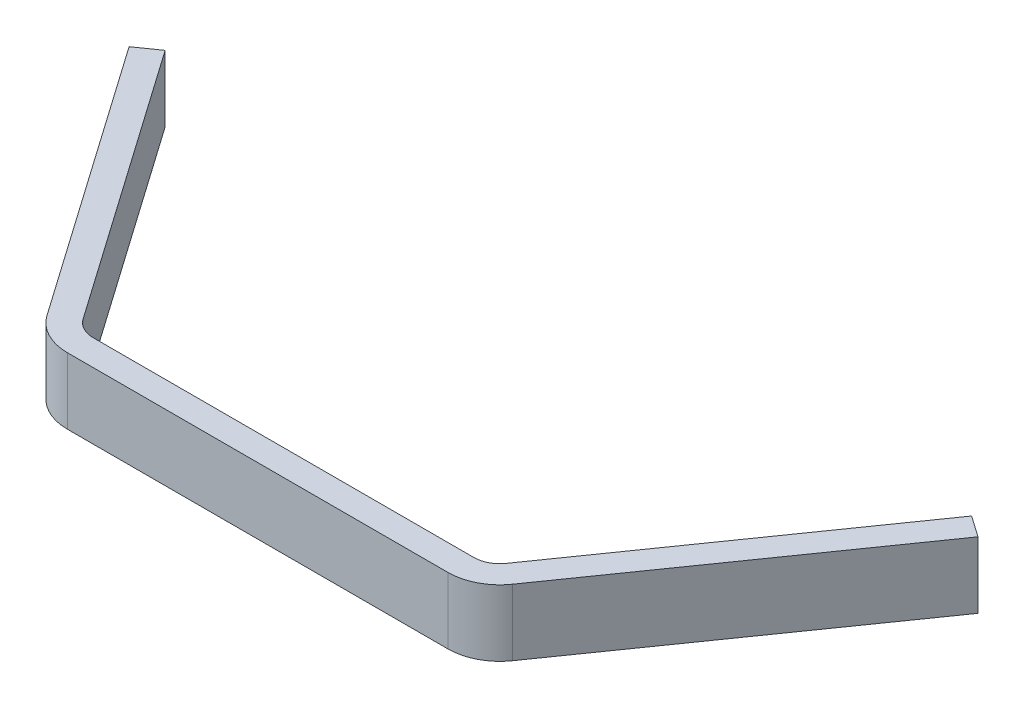
SolidWorks part; units mm, degrees
ref_plane "Front Plane" through (0, 0, 0) normal (0, 0, 1) x (1, 0, 0)
ref_plane "Top Plane" through (0, 0, 0) normal (0, 1, 0) x (1, 0, 0)
ref_plane "Right Plane" through (0, 0, 0) normal (1, 0, 0) x (0, 0, -1)
sketch "Sketch1" plane through (0, 0, 0) normal (0, 1, 0) x (1, 0, 0)
  line L0 (-56.1097, 38.9065) -> (-28.5399, -0.4672) construction
  line L9 (-53.5089, 40.7276) -> (-25.9391, 1.3539) construction
  line L10 (25.9391, 1.3539) -> (53.5089, 40.7276) construction
  line L11 (28.5399, -0.4672) -> (56.1097, 38.9065) construction
  line L12 (-49.4458, 34.925) -> (-25.9391, 1.3539)
  line L13 (-23.3383, 0) -> (23.3383, 0)
  line L14 (25.9391, 1.3539) -> (49.4458, 34.925)
  line L15 (-56.1097, 38.9065) -> (-26.6439, -3.175)
  line L16 (26.6439, -3.175) -> (56.1097, 38.9065)
  line L17 (-26.6439, -3.175) -> (26.6439, -3.175)
  line L18 (-52.0466, 33.1039) -> (-28.5399, -0.4672)
  line L19 (28.5399, -0.4672) -> (52.0466, 33.1039)
  line L20 (-23.3383, -3.175) -> (23.3383, -3.175)
  line L21 (-52.0466, 33.1039) -> (-49.4458, 34.925)
  line L22 (0, -3.175) -> (0, 22.2949) construction
  line L23 (52.0466, 33.1039) -> (49.4458, 34.925)
  arc A4 (28.5399, -0.4672) -> (23.3383, -3.175) centre (23.3383, 3.175) cw
  arc A5 (-28.5399, -0.4672) -> (-23.3383, -3.175) centre (-23.3383, 3.175) ccw
  arc A6 (-25.9391, 1.3539) -> (-23.3383, 0) centre (-23.3383, 3.175) ccw
  arc A7 (25.9391, 1.3539) -> (23.3383, 0) centre (23.3383, 3.175) cw
  dimension "D2" = 6.35
  dimension "D1" = 1.27
  dimension "D4" = 38.1
  dimension "D3" = 3.175
extrude "Boss-Extrude1" add sketch "Sketch1" along normal offset from surface 1.27 and the other way offset from surface (2.54 mm away) 1.27
